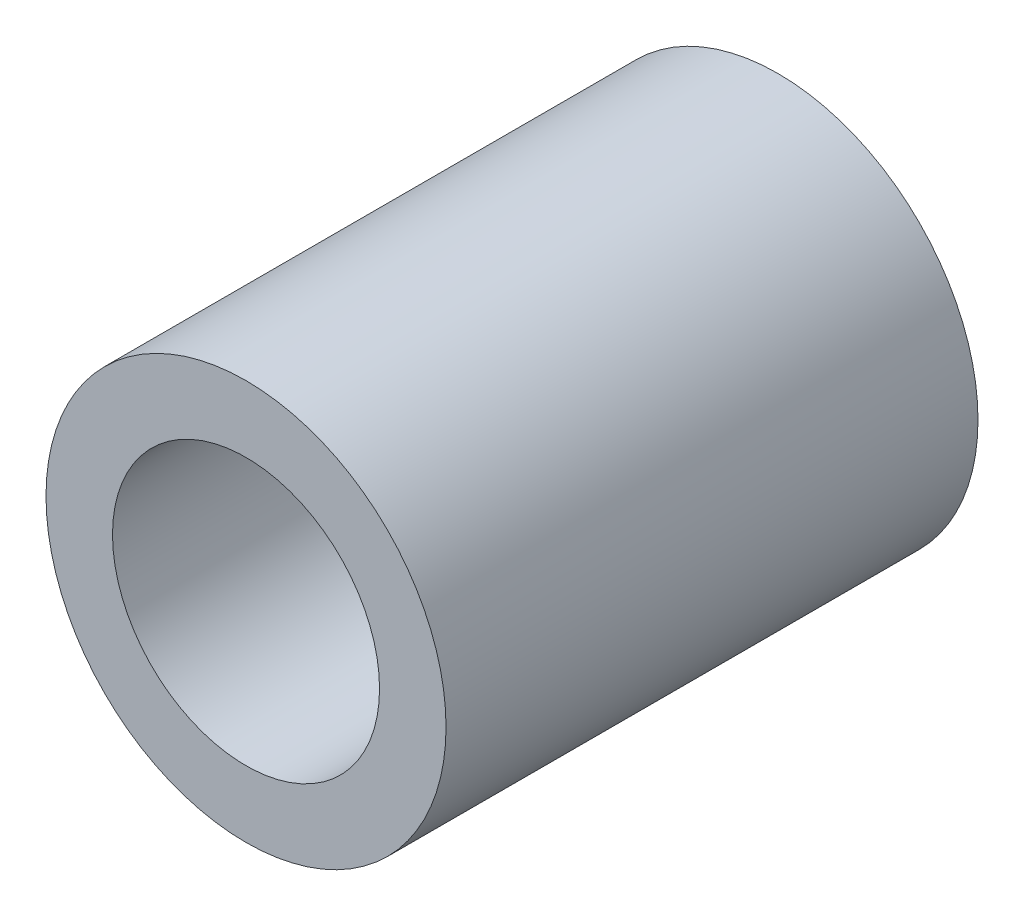
SolidWorks part; units mm, degrees
ref_plane "Front Plane" through (0, 0, 0) normal (0, 0, 1) x (1, 0, 0)
ref_plane "Top Plane" through (0, 0, 0) normal (0, 1, 0) x (1, 0, 0)
ref_plane "Right Plane" through (0, 0, 0) normal (1, 0, 0) x (0, 0, -1)
sketch "Sketch1" plane through (0, 0, 0) normal (0, 0, 1) x (1, 0, 0)
  circle A0 centre (0, 0) radius 4.7752
  circle A1 centre (0, 0) radius 3.1877
  dimension "D1" = 9.5504
  dimension "ID" = 6.3754
extrude "Extrude1" add sketch "Sketch1" along normal mid plane 12.7
sketch "Sketch2" plane through (0, 0, 0) normal (1, 0, 0) x (0, 0, -1)
  line L0 (-6.35, -3.1877) -> (6.35, -3.1877) construction
  line L3 (6.35, 3.1877) -> (-6.35, 3.1877) construction
  line L5 (-6.35, -3.1877) -> (6.35, -3.1877)
  line L6 (6.35, 3.1877) -> (-6.35, 3.1877)
sketch "Sketch4" plane through (0, 0, 6.35) normal (0, 0, 1) x (1, 0, 0)
  line L0 (0, 0) -> (-2.254, 2.254)
  line L1 (0, -55) -> (0, 55) construction
  circle A0 centre (0, 0) radius 3.1877 construction
  dimension "D1" = 45
